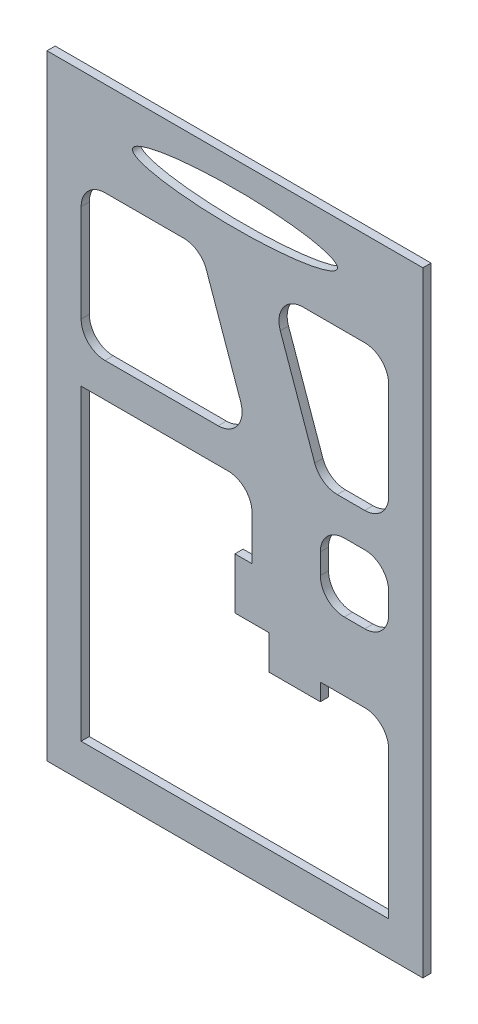
SolidWorks part; units mm, degrees
material "PBT General Purpose"
ref_plane "Front Plane" through (0, 0, 0) normal (0, 0, 1) x (1, 0, 0)
ref_plane "Top Plane" through (0, 0, 0) normal (0, 1, 0) x (1, 0, 0)
ref_plane "Right Plane" through (0, 0, 0) normal (1, 0, 0) x (0, 0, -1)
sketch "Sketch1" plane through (0, 0, 0) normal (0, 0, 1) x (1, 0, 0)
  line L0 (-1, 1) -> (-1, 6)
  line L1 (0, 0) -> (-11, 0)
  line L2 (0, 0) -> (0, 11)
  line L3 (0, 11) -> (-11, 11) construction
  line L4 (-11, 0) -> (-11, 11)
  line L5 (-3, 6) -> (-1, 6)
  line L6 (-3, 6) -> (-3, 5.5)
  line L7 (-3, 5.5) -> (-4.5, 5.5)
  line L8 (-4.5, 5.5) -> (-4.5, 6.5)
  line L9 (-4.5, 6.5) -> (-5.5, 6.5)
  line L10 (-5.5, 6.5) -> (-5.5, 8)
  line L11 (-5.5, 8) -> (-5, 8)
  line L12 (-5, 8) -> (-5, 10)
  line L13 (-5, 10) -> (-10, 10)
  line L14 (-1, 1) -> (-10, 1)
  line L15 (-10, 1) -> (-10, 10)
  line L18 (-11, 11) -> (-11, 18)
  line L19 (-11, 18) -> (0, 18)
  line L20 (0, 11) -> (0, 18)
  dimension "D1" = 11
  dimension "D2" = 11
  dimension "D3" = 1
  dimension "D4" = 1
  dimension "1" = 1
  dimension "D5" = 5
  dimension "D6" = 5
  dimension "D7" = 1
  dimension "D8" = 2
  dimension "D9" = 1.5
  dimension "D10" = 1.5
  dimension "D11" = 0.5
  dimension "D12" = 0.5
  dimension "D13" = 2
  dimension "D14" = 7
extrude "Boss-Extrude1" add sketch "Sketch1" along normal mid plane 0.24
sketch "Sketch3" plane through (0, 0, 0.12) normal (0, 0, 1) x (1, 0, 0)
  line L0 (-11, 16.75) -> (0, 16.75) construction
  line L1 (-11, 18) -> (-11, 0) construction
  line L2 (0, 0) -> (0, 18) construction
  line L3 (0, 18) -> (-11, 18) construction
  line L4 (-1, 1) -> (-1, 6) construction
  line L5 (-10, 11) -> (-5, 11)
  line L6 (-10, 11) -> (-10, 15.25)
  line L7 (-10, 15.25) -> (-6.5, 15.25)
  line L8 (-1, 11) -> (-1, 15.25)
  line L9 (-1, 10) -> (-3, 10)
  line L10 (-1, 10) -> (-1, 8)
  line L11 (-1, 8) -> (-3, 8)
  line L12 (-3, 10) -> (-3, 8)
  line L13 (-3, 6) -> (-3, 5.5) construction
  line L14 (-10, 10) -> (-10, 1) construction
  line L15 (-5, 10) -> (-10, 10) construction
  line L16 (-5.5, 8) -> (-5, 8) construction
  line L17 (-5, 11) -> (-6.5, 15.25)
  line L18 (-3, 11) -> (-4.5, 15.25)
  line L19 (-3, 11) -> (-1, 11)
  line L20 (-6.5, 15.25) -> (-4.5, 15.25) construction
  line L22 (-4.5, 15.25) -> (-1, 15.25)
  ellipse E0 centre (-5.5, 16.75) end of major axis (-8.5, 16.75) minor radius 0.5
  point P36 (-5.2375, 15.25)
  point P37 (-5.5, 15.25)
  dimension "D1" = 1.25
  dimension "D2" = 0.5
  dimension "D3" = 3
  dimension "D4" = 1
  dimension "D5" = 1
extrude "Cut-Extrude1" cut sketch "Sketch3" against normal through all both and the other way through all
fillet "Fillet1" radius 0.7 14 edges at (-5, 10, 0) (-1, 6, 0) (-3, 8, 0) (-1, 8, 0) (-1, 10, 0) (-3, 10, 0) (-4.5, 15.25, 0) (-3, 11, 0) (-10, 11, 0) (-5, 11, 0) (-1, 11, 0) (-1, 15.25, 0) (-6.5, 15.25, 0) (-10, 15.25, 0)
